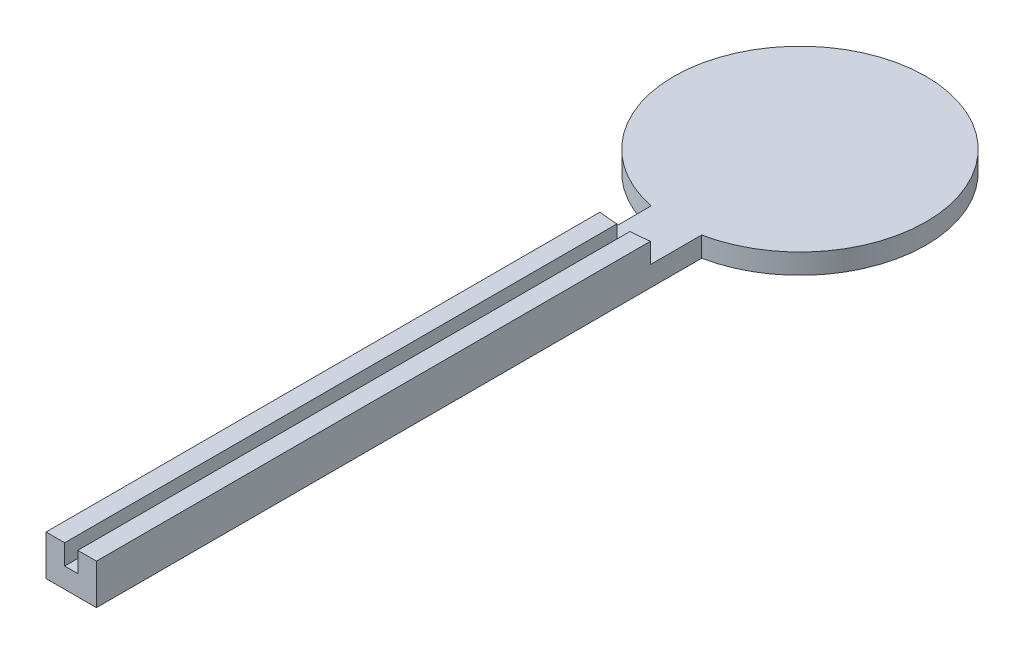
SolidWorks part; units mm, degrees
ref_plane "Front Plane" through (0, 0, 0) normal (0, 0, 1) x (1, 0, 0)
ref_plane "Top Plane" through (0, 0, 0) normal (0, 1, 0) x (1, 0, 0)
ref_plane "Right Plane" through (0, 0, 0) normal (1, 0, 0) x (0, 0, -1)
sketch "Sketch1" plane through (0, 0, 0) normal (0, 1, 0) x (1, 0, 0)
  line L0 (2.5, -72.2474) -> (-2.5, -72.2474)
  line L1 (2.5, -72.2474) -> (2.5, -12.2474)
  line L2 (-2.5, -72.2474) -> (-2.5, -12.2474)
  arc A0 (2.5, -12.2474) -> (-2.5, -12.2474) centre (0, 0) ccw
  point P1 (0, -72.2474)
  point P6 (0, 0)
  dimension "D2" = 25
  dimension "D1" = 5
  dimension "D3" = 60
extrude "Boss-Extrude1" add sketch "Sketch1" along normal blind 4
sketch "Sketch3" plane through (0, 4, 0) normal (0, 1, 0) x (1, 0, 0)
  circle A0 centre (0, 0) radius 17.5
extrude "Cut-Extrude1" cut sketch "Sketch3" against normal blind 2
sketch "Sketch4" plane through (0, 4, 0) normal (0, 1, 0) x (1, 0, 0)
  line L0 (-0.65, -17.4879) -> (-0.65, -72.2474)
  line L2 (-0.65, -72.2474) -> (0.65, -72.2474)
  line L3 (0.65, -72.2474) -> (0.65, -17.4879)
  line L4 (-2.5, -72.2474) -> (2.5, -72.2474) construction
  arc A0 (-2.5, -17.3205) -> (2.5, -17.3205) centre (0, 0) ccw construction
  arc A1 (-0.65, -17.4879) -> (0.65, -17.4879) centre (0, 0) ccw
  point P9 (0, 0)
  point P10 (0, 0)
  point P11 (0, -72.2474)
  point P12 (0, -72.2474)
  dimension "D1" = 1.3
extrude "Cut-Extrude2" cut sketch "Sketch4" against normal blind 2
